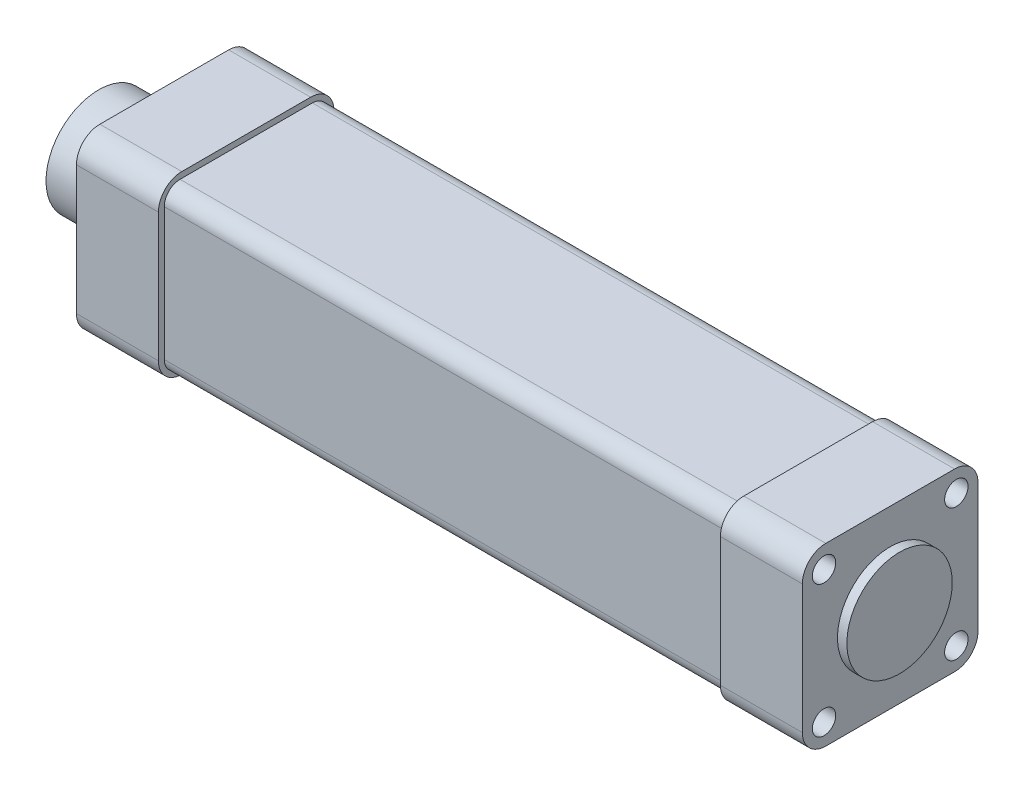
SolidWorks part; units mm, degrees
ref_plane "Front Plane" through (0, 0, 0) normal (0, 0, 1) x (1, 0, 0)
ref_plane "Top Plane" through (0, 0, 0) normal (0, 1, 0) x (1, 0, 0)
ref_plane "Right Plane" through (0, 0, 0) normal (1, 0, 0) x (0, 0, -1)
sketch "Esquisse1" plane through (0, 0, 0) normal (1, 0, 0) x (0, 0, -1)
  line L0 (0, 52.0635) -> (0, -40.917) construction
  line L1 (35, 28.25) -> (35, -28.25)
  line L17 (-28.25, -35) -> (28.25, -35)
  line L18 (-35, 28.25) -> (-35, -28.25)
  line L19 (28.25, 35) -> (-28.25, 35)
  arc A0 (35, -28.25) -> (28.25, -35) centre (28.25, -28.25) cw
  circle A1 centre (28.25, -28.25) radius 5
  circle A2 centre (28.25, 28.25) radius 5
  arc A3 (35, 28.25) -> (28.25, 35) centre (28.25, 28.25) ccw
  arc A4 (-35, -28.25) -> (-28.25, -35) centre (-28.25, -28.25) ccw
  circle A5 centre (-28.25, -28.25) radius 5
  circle A6 centre (-28.25, 28.25) radius 5
  arc A7 (-35, 28.25) -> (-28.25, 35) centre (-28.25, 28.25) cw
  circle A8 centre (0, 0) radius 31.5
  point P9 (0, -35)
  point P15 (0, 35)
  dimension "D2" = 56.5
  dimension "D4" = 70
  dimension "D5" = 70
  dimension "D6" = 35
  dimension "D3" = 56.5
  dimension "D14" = 63
  dimension "D7" = 10
  dimension "D8" = 10
extrude "Boss.-Extru.1" add sketch "Esquisse1" along normal blind 240
sketch "Esquisse3" plane through (240, 0, 0) normal (1, 0, 0) x (0, 0, -1)
  line L1 (-27.5, -37.5) -> (27.5, -37.5)
  line L2 (-37.5, -27.5) -> (-37.5, 27.5)
  line L3 (-27.5, 37.5) -> (27.5, 37.5)
  line L4 (37.5, -27.5) -> (37.5, 27.5)
  arc A0 (27.5, -37.5) -> (37.5, -27.5) centre (27.5, -27.5) ccw
  arc A1 (-27.5, -37.5) -> (-37.5, -27.5) centre (-27.5, -27.5) cw
  arc A2 (-37.5, 27.5) -> (-27.5, 37.5) centre (-27.5, 27.5) cw
  arc A3 (27.5, 37.5) -> (37.5, 27.5) centre (27.5, 27.5) cw
  circle A4 centre (-28.25, 28.25) radius 5
  circle A5 centre (28.25, 28.25) radius 5
  circle A6 centre (28.25, -28.25) radius 5
  circle A7 centre (-28.25, -28.25) radius 5
  point P0 (0, 0)
  dimension "D3" = 10
  dimension "D4" = 37.5
  dimension "D7" = 10
  dimension "D1" = 75
  dimension "D2" = 75
  dimension "D6" = 37.5
  dimension "D5" = 4
extrude "Boss.-Extru.3" add sketch "Esquisse3" along normal blind 35
sketch "Esquisse4" plane through (275, 0, 0) normal (1, 0, 0) x (0, 0, -1)
  circle A0 centre (0, 0) radius 22.5
  dimension "D1" = 45
extrude "Boss.-Extru.4" add sketch "Esquisse4" along normal blind 4
sketch "Esquisse5" plane through (0, 0, 0) normal (-1, 0, 0) x (0, 0, 1)
  line L0 (-27.5, 37.5) -> (27.5, 37.5) construction
  line L1 (27.5, -37.5) -> (-27.5, -37.5)
  line L2 (37.5, -27.5) -> (37.5, 27.5)
  line L3 (27.5, 37.5) -> (-27.5, 37.5)
  line L4 (-37.5, -27.5) -> (-37.5, 27.5)
  line L5 (27.5, -37.5) -> (-27.5, -37.5) construction
  arc A0 (37.5, 27.5) -> (27.5, 37.5) centre (27.5, 27.5) ccw
  arc A1 (27.5, -37.5) -> (37.5, -27.5) centre (27.5, -27.5) ccw
  arc A2 (-27.5, -37.5) -> (-37.5, -27.5) centre (-27.5, -27.5) cw
  arc A3 (-27.5, 37.5) -> (-37.5, 27.5) centre (-27.5, 27.5) ccw
  circle A4 centre (-28.25, 28.25) radius 5
  circle A5 centre (28.25, 28.25) radius 5
  circle A6 centre (28.25, -28.25) radius 5
  circle A7 centre (-28.25, -28.25) radius 5
  point P0 (0, 0)
  dimension "D1" = 10
extrude "Boss.-Extru.5" add sketch "Esquisse5" along normal blind 35
sketch "Esquisse6" plane through (-35, 0, 0) normal (-1, 0, 0) x (0, 0, 1)
  circle A0 centre (0, 0) radius 22.5
  dimension "D1" = 45
extrude "Boss.-Extru.6" add sketch "Esquisse6" along normal blind 4
sketch "Esquisse7" plane through (-39, 0, 0) normal (-1, 0, 0) x (0, 0, 1)
  circle A0 centre (0, 0) radius 22.5
  dimension "D1" = 45
extrude "Boss.-Extru.7" add sketch "Esquisse7" along normal blind 24
sketch "Esquisse8" plane through (-63, 0, 0) normal (-1, 0, 0) x (0, 0, 1)
  circle A0 centre (0, 0) radius 10
  dimension "D1" = 20
extrude "Enlèv. mat.-Extru.1" cut sketch "Esquisse8" against normal up to next
